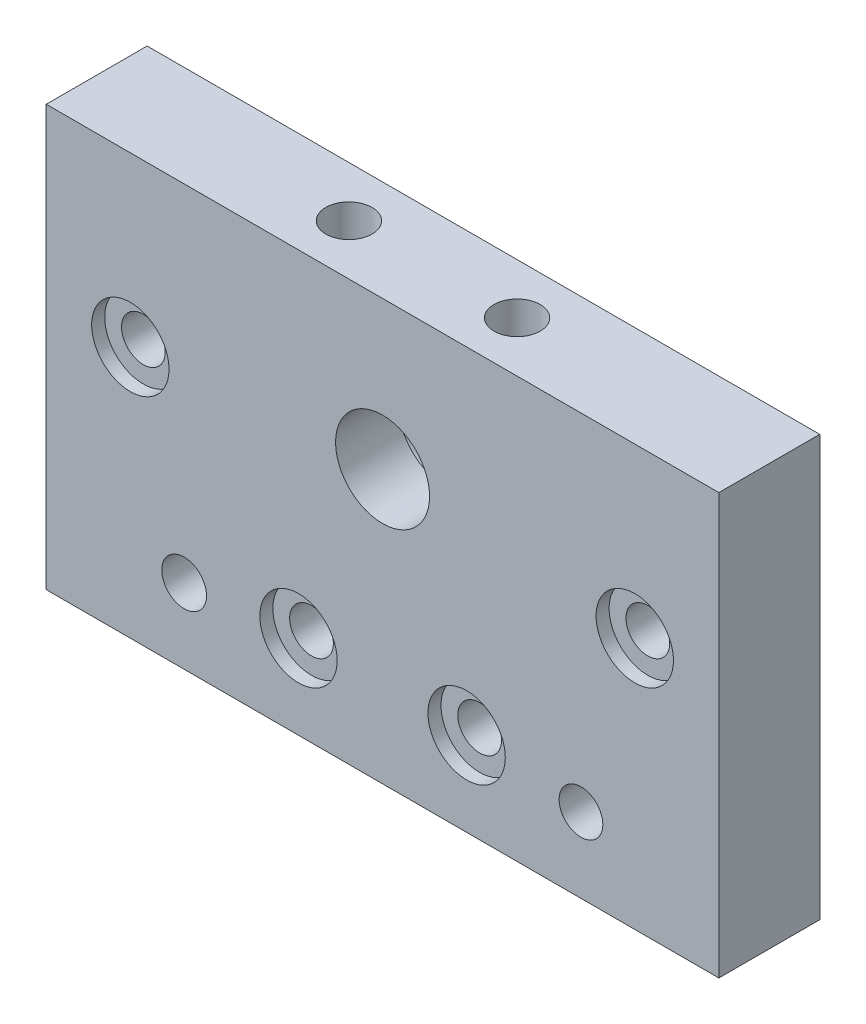
SolidWorks part; units mm, degrees
material "ABS"
ref_plane "Alzado" through (0, 0, 0) normal (0, 0, 1) x (1, 0, 0)
ref_plane "Planta" through (0, 0, 0) normal (0, 1, 0) x (1, 0, 0)
ref_plane "Vista lateral" through (0, 0, 0) normal (1, 0, 0) x (0, 0, -1)
sketch "Croquis1" plane through (0, 0, 0) normal (0, 0, 1) x (1, 0, 0)
  line L0 (0, 0) -> (80, 0)
  line L1 (0, 0) -> (0, 50)
  line L2 (0, 50) -> (80, 50)
  line L3 (80, 50) -> (80, 0)
  circle A0 centre (10, 30) radius 2.6
  circle A1 centre (70, 30) radius 2.6
  circle A2 centre (40, 32.4) radius 5.59
  circle A3 centre (16.4, 8.9) radius 2.6617
  circle A4 centre (30, 10) radius 2.6
  circle A5 centre (50, 10) radius 2.6
  circle A6 centre (63.6, 8.9) radius 2.6
  dimension "D4" = 20
  dimension "D5" = 5.2
  dimension "D7" = 11.18
  dimension "D10" = 5.2
  dimension "D11" = 5.3234
  dimension "D12" = 16.4
  dimension "D13" = 8.9
  dimension "D17" = 5.2
  dimension "D18" = 5.2
  dimension "D19" = 16.4
  dimension "D20" = 5.2
  dimension "D1" = 80
  dimension "D2" = 50
  dimension "D3" = 10
  dimension "D6" = 10
  dimension "D8" = 17.6
  dimension "D9" = 20
  dimension "D14" = 30
  dimension "D15" = 10
  dimension "D16" = 30
  dimension "D21" = 40
extrude "Saliente-Extruir1" add sketch "Croquis1" along normal blind 12
sketch "Croquis2" plane through (0, 0, 12) normal (0, 0, 1) x (1, 0, 0)
  circle A0 centre (10, 30) radius 4.6
  circle A1 centre (70, 30) radius 4.6
  circle A2 centre (30, 10) radius 4.6
  circle A3 centre (50, 10) radius 4.6
  dimension "D1" = 9.2
  dimension "D2" = 9.2
  dimension "D3" = 9.2
  dimension "D4" = 9.2
extrude "Cortar-Extruir1" cut sketch "Croquis2" against normal blind 1.55
sketch "Croquis4" plane through (0, 0, 0) normal (0, 0, -1) x (-1, 0, 0)
  circle A0 centre (-40, 32.4) radius 8.05
  dimension "D1" = 16.1
extrude "Cortar-Extruir2" cut sketch "Croquis4" against normal blind 4.5
sketch "Croquis5" plane through (0, 50, 0) normal (0, 1, 0) x (1, 0, 0)
  line L0 (0, -12) -> (0, 0) construction
  line L1 (80, 0) -> (0, 0) construction
  circle A0 centre (30, -6) radius 1.1961
  dimension "D1" = 30
  dimension "D2" = 6
hole_wizard "Taladro de margen para M51" positions "Croquis3D1" profile "Croquis6" hole size "M5" standard "Ansi Metric"
sketch3d "Croquis3D1"
  point P0 (30, 50, 6)
sketch "Croquis6" plane through (30, 50, 6) normal (1, 0, 0) x (0, 0, 1)
  line L0 (0, 0) -> (0, 11.6524)
  line L1 (0, 11.6524) -> (2.75, 10)
  line L2 (2.75, 10) -> (2.75, 0)
  line L5 (2.75, 0) -> (0, 0)
  line L10 (0, 11.6524) -> (-2.75, 10) construction
  line L11 (0, -6.35) -> (0, 107.95) construction
  dimension "Diámetro de taladro" = 5.5
  dimension "Profundidad de taladro" = 10
  dimension "Ángulo de perforador" = 118
sketch "Croquis7" plane through (0, 50, 0) normal (0, 1, 0) x (1, 0, 0)
  line L0 (80, -12) -> (80, 0) construction
  line L1 (80, -12) -> (0, -12) construction
  circle A0 centre (50, -6) radius 4.6045
  dimension "D1" = 30
  dimension "D2" = 6
hole_wizard "Taladro de margen para M52" positions "Croquis3D2" profile "Croquis8" hole size "M5" standard "Ansi Metric"
sketch3d "Croquis3D2"
  point P0 (50, 50, 6)
sketch "Croquis8" plane through (50, 50, 6) normal (1, 0, 0) x (0, 0, 1)
  line L0 (0, 0) -> (0, 11.6524)
  line L1 (0, 11.6524) -> (2.75, 10)
  line L2 (2.75, 10) -> (2.75, 0)
  line L5 (2.75, 0) -> (0, 0)
  line L10 (0, 11.6524) -> (-2.75, 10) construction
  line L11 (0, -6.35) -> (0, 107.95) construction
  dimension "Diámetro de taladro" = 5.5
  dimension "Profundidad de taladro" = 10
  dimension "Ángulo de perforador" = 118
